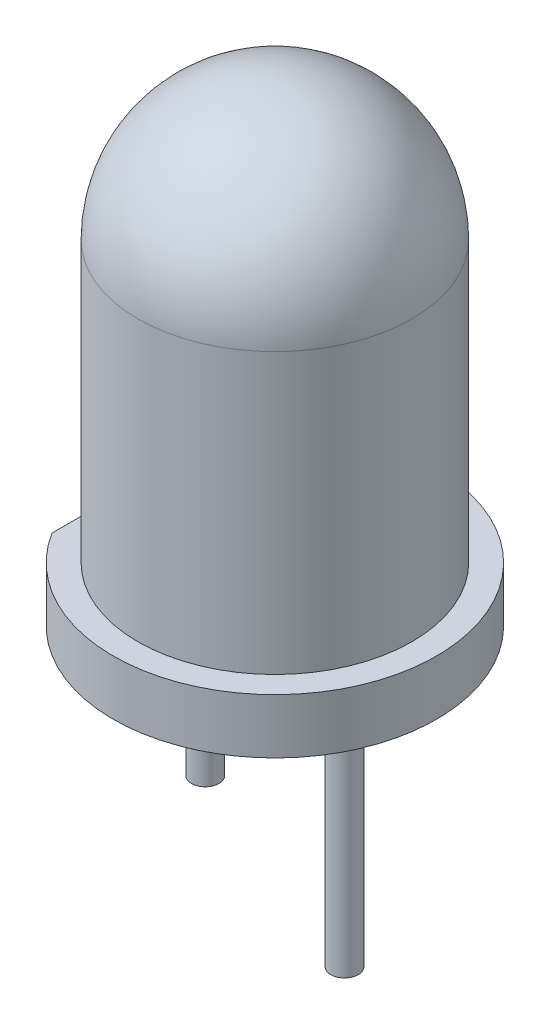
SolidWorks part; units mm, degrees
ref_plane "Front Plane" through (0, 0, 0) normal (0, 0, 1) x (1, 0, 0)
ref_plane "Top Plane" through (0, 0, 0) normal (0, 1, 0) x (1, 0, 0)
ref_plane "Right Plane" through (0, 0, 0) normal (1, 0, 0) x (0, 0, -1)
sketch "Sketch1" plane through (0, 0, 0) normal (0, 1, 0) x (1, 0, 0)
  circle A0 centre (0, 0) radius 2.95
extrude "Boss-Extrude1" add sketch "Sketch1" along normal blind 1
sketch "Sketch2" plane through (0, 1, 0) normal (0, 1, 0) x (1, 0, 0)
  circle A0 centre (0, 0) radius 2.5
extrude "Boss-Extrude2" add sketch "Sketch2" along normal blind 7.6
fillet "Fillet1" radius 2.5 1 edges at (0, 8.6, 2.5)
sketch "Sketch3" plane through (0, 0, 0) normal (0, -1, 0) x (1, 0, 0)
  circle A0 centre (-1.27, 0) radius 0.25
  circle A1 centre (1.27, 0) radius 0.25
  dimension "D1" = 2.54
  dimension "D3" = 0.5
  dimension "D4" = 0.5
  dimension "D2" = 1.27
extrude "Boss-Extrude3" add sketch "Sketch3" along normal blind 4.75
sketch "Sketch4" plane through (0, -4.75, 0) normal (0, -1, 0) x (1, 0, 0)
  circle A0 centre (-1.27, 0) radius 0.25
extrude "Cut-Extrude1" cut sketch "Sketch4" against normal blind 1.75
sketch "Sketch5" plane through (0, 1, 0) normal (0, 1, 0) x (1, 0, 0)
  line L2 (-2.5, 0) -> (-2.5, 1.9835)
  line L3 (-2.5, 1.9835) -> (-3.126, 1.9835)
  line L4 (-3.126, 0) -> (-3.126, 1.9835)
  line L6 (-2.5, 0) -> (-2.5, -2.1845)
  line L7 (-2.5, -2.1845) -> (-3.126, -2.1845)
  line L8 (-3.126, 0) -> (-3.126, -2.1845)
  circle A0 centre (0, 0) radius 2.5 construction
extrude "Cut-Extrude2" cut sketch "Sketch5" against normal through all
